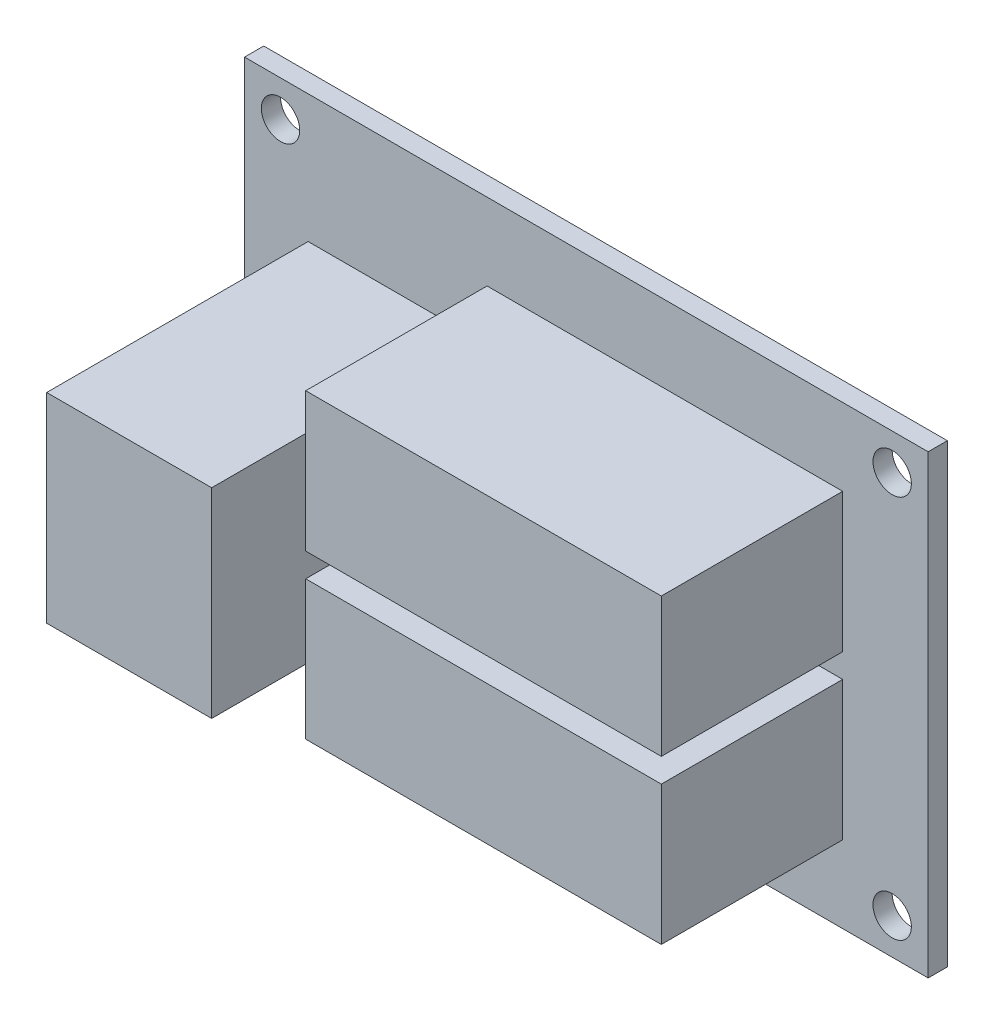
SolidWorks part; units mm, degrees
ref_plane "Front Plane" through (0, 0, 0) normal (0, 0, 1) x (1, 0, 0)
ref_plane "Top Plane" through (0, 0, 0) normal (0, 1, 0) x (1, 0, 0)
ref_plane "Right Plane" through (0, 0, 0) normal (1, 0, 0) x (0, 0, -1)
sketch "Sketch1" plane through (0, 0, 0) normal (0, 0, 1) x (1, 0, 0)
  line L1 (-28.5, 19) -> (28.5, 19)
  line L2 (-28.5, 19) -> (-28.5, -19)
  line L3 (-28.5, -19) -> (28.5, -19)
  line L4 (28.5, 19) -> (28.5, -19)
  line L5 (-28.5, 19) -> (28.5, -19) construction
  line L6 (-28.5, -19) -> (28.5, 19) construction
  line L7 (-25.5, 16) -> (25.5, 16) construction
  line L8 (-25.5, 16) -> (-25.5, -16) construction
  line L9 (-25.5, -16) -> (25.5, -16) construction
  line L10 (25.5, 16) -> (25.5, -16) construction
  line L11 (-25.5, 16) -> (25.5, -16) construction
  line L12 (-25.5, -16) -> (25.5, 16) construction
  circle A0 centre (-25.5, 16) radius 1.6
  circle A1 centre (-25.5, -16) radius 1.6
  circle A2 centre (25.5, -16) radius 1.6
  circle A3 centre (25.5, 16) radius 1.6
  point P0 (0, 0)
  point P6 (0, 0)
  dimension "D5" = 3.2
  dimension "D1" = 38
  dimension "D2" = 57
  dimension "D3" = 51
  dimension "D4" = 32
extrude "Boss-Extrude1" add sketch "Sketch1" along normal blind 1.6
sketch "Sketch2" plane through (0, 0, 1.6) normal (0, 0, 1) x (1, 0, 0)
  line L0 (-16.3206, 0) -> (0, 0) construction
  line L1 (-23.1994, 8.3311) -> (-9.4418, 8.3311)
  line L2 (-23.1994, 8.3311) -> (-23.1994, -8.3311)
  line L3 (-23.1994, -8.3311) -> (-9.4418, -8.3311)
  line L4 (-9.4418, 8.3311) -> (-9.4418, -8.3311)
  line L5 (-23.1994, 8.3311) -> (-9.4418, -8.3311) construction
  line L6 (-23.1994, -8.3311) -> (-9.4418, 8.3311) construction
  line L7 (21.3741, 12.5821) -> (-8.2763, 12.5821)
  line L8 (21.3741, 12.5821) -> (21.3741, 1)
  line L9 (21.3741, 1) -> (-8.2763, 1)
  line L10 (-8.2763, 12.5821) -> (-8.2763, 1)
  line L11 (21.3741, 12.5821) -> (-8.2763, 1) construction
  line L12 (21.3741, 1) -> (-8.2763, 12.5821) construction
  line L13 (21.3741, -1) -> (-8.2763, -1)
  line L14 (21.3741, -1) -> (21.3741, -12.5821)
  line L15 (21.3741, -12.5821) -> (-8.2763, -12.5821)
  line L16 (-8.2763, -1) -> (-8.2763, -12.5821)
  line L17 (21.3741, -1) -> (-8.2763, -12.5821) construction
  line L18 (21.3741, -12.5821) -> (-8.2763, -1) construction
  point P0 (-16.3206, 0)
  point P5 (6.5489, 6.791)
  point P10 (6.5489, -6.791)
  point P15 (-8.2763, -12.8915)
  point P16 (-24.6743, 8.5084)
  point P17 (21.3741, -12.5821)
  point P18 (0, 0)
  point P19 (-16.3206, 0)
  dimension "D1" = 1
  dimension "D2" = 1
extrude "Boss-Extrude2" add sketch "Sketch2" along normal blind 21.8
sketch "Sketch3" plane through (0, -12.5821, 0) normal (0, -1, 0) x (-1, 0, 0)
  line L0 (-21.3741, -23.4) -> (-21.3741, -1.6) construction
  line L1 (8.2763, -23.4) -> (-21.3741, -23.4)
  line L2 (8.2763, -23.4) -> (8.2763, -16.7229)
  line L3 (8.2763, -16.7229) -> (-21.3741, -16.7229)
  line L4 (-21.3741, -23.4) -> (-21.3741, -16.7229)
extrude "Cut-Extrude1" cut sketch "Sketch3" against normal through all
